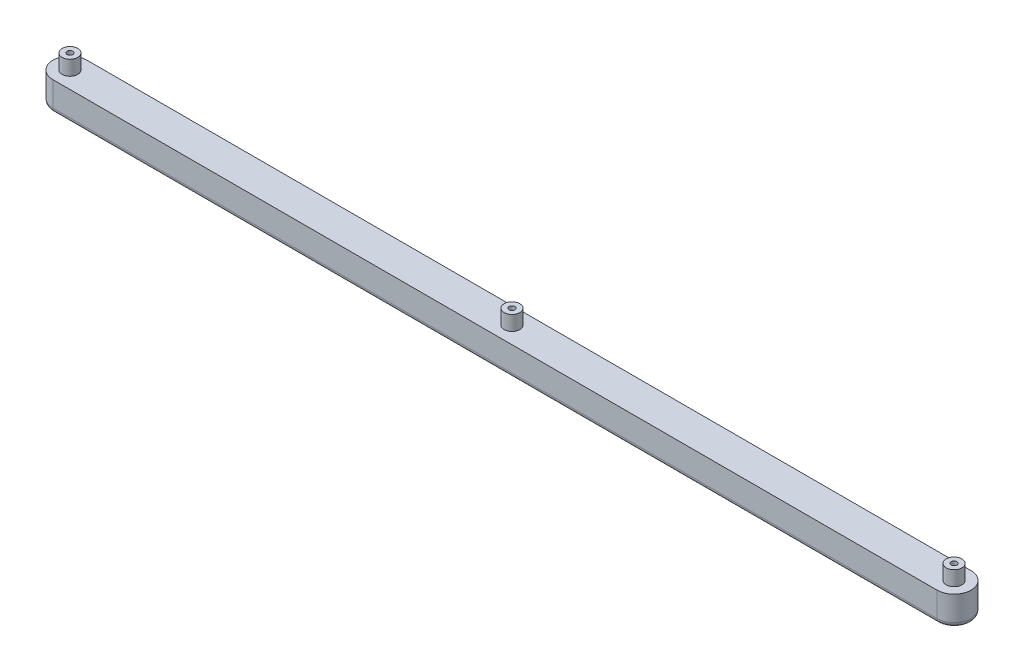
SolidWorks part; units mm, degrees
ref_plane "Alzado" through (0, 0, 0) normal (0, 0, 1) x (1, 0, 0)
ref_plane "Planta" through (0, 0, 0) normal (0, 1, 0) x (1, 0, 0)
ref_plane "Vista lateral" through (0, 0, 0) normal (1, 0, 0) x (0, 0, -1)
sketch "Croquis2" plane through (0, 0, 0) normal (0, 1, 0) x (1, 0, 0)
  line L0 (-90, 0) -> (90, 0) construction
  line L2 (-90, -3.45) -> (90, -3.45)
  line L3 (0, 0) -> (0, 30) construction
  line L10 (-90, 3.45) -> (90, 3.45)
  arc A8 (-90, 3.45) -> (-90, -3.45) centre (-90, 0) ccw
  arc A10 (90, -3.45) -> (90, 3.45) centre (90, 0) ccw
  point P4 (0, 0)
  point P6 (0, 30)
  point P7 (-90, 0)
  point P9 (105, 0)
  point P10 (-56.205, 0)
  point P15 (63.105, 0)
  point P30 (4.5, 30)
  dimension "D2" = 0
  dimension "D3" = 180
extrude "Saliente-Extruir1" add sketch "Croquis2" along normal mid plane 6
sketch "Croquis3" plane through (0, 3, 0) normal (0, 1, 0) x (1, 0, 0)
  circle A0 centre (-90, 0) radius 1.59
  circle A1 centre (90, 0) radius 1.59
  circle A2 centre (0, 0) radius 1.59
  dimension "D1" = 3.18
  dimension "D2" = 3.18
  dimension "D4" = 90
  dimension "D5" = 3.18
  dimension "D3" = 180
extrude "Saliente-Extruir2" add sketch "Croquis3" along normal blind 3
fillet "Redondeo1" radius 1 4 edges at (0, -3, 3.45) (0, -3, -3.45) (-93.45, -3, 0) (93.45, -3, 0)
sketch "Croquis4" plane through (0, 6, 0) normal (0, 1, 0) x (1, 0, 0)
  circle A0 centre (90, 0) radius 0.59
  circle A1 centre (90, 0) radius 1.59 construction
  circle A2 centre (-90, 0) radius 0.59
  circle A3 centre (-90, 0) radius 1.59 construction
  circle A6 centre (0, 0) radius 0.59
  circle A7 centre (0, 0) radius 0.59
  dimension "D1" = 1
  dimension "D2" = 1
  dimension "D3" = 1
extrude "Cortar-Extruir1" cut sketch "Croquis4" against normal through all
